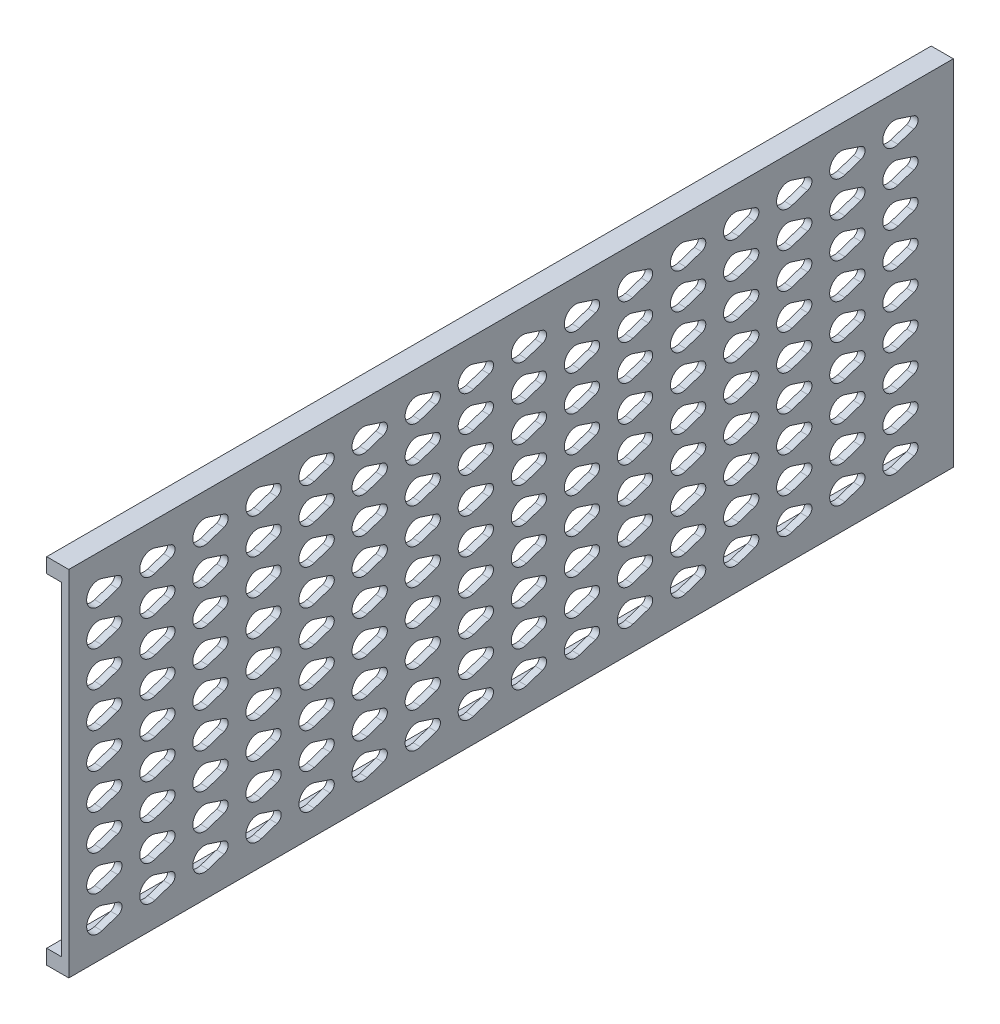
SolidWorks part; units mm, degrees
ref_plane "Front Plane" through (0, 0, 0) normal (1, 0, 0) x (0, 1, 0)
ref_plane "Top Plane" through (0, 0, 0) normal (0, 0, 1) x (0, 1, 0)
ref_plane "Right Plane" through (0, 0, 0) normal (0, 1, 0) x (-1, 0, 0)
sketch "Sketch1" plane through (0, 0, 0) normal (1, 0, 0) x (0, 1, 0)
  line L1 (-76.2, -190.5) -> (76.2, -190.5)
  line L2 (-76.2, -190.5) -> (-76.2, 190.5)
  line L3 (-76.2, 190.5) -> (76.2, 190.5)
  line L4 (76.2, -190.5) -> (76.2, 190.5)
  line L5 (-76.2, -190.5) -> (76.2, 190.5) construction
  line L6 (-76.2, 190.5) -> (76.2, -190.5) construction
  point P0 (0, 0)
  dimension "D1" = 152.4
  dimension "D2" = 381
extrude "Boss-Extrude1" add sketch "Sketch1" along normal blind 3.175
sketch "Sketch2" plane through (0, 0, 0) normal (-1, 0, 0) x (0, -1, 0)
  line L5 (-76.2, 190.5) -> (76.2, 190.5) construction
  line L6 (-76.2, -190.5) -> (-69.85, -190.5)
  line L7 (-76.2, -190.5) -> (-76.2, 190.5)
  line L8 (-76.2, 190.5) -> (-69.85, 190.5)
  line L9 (-69.85, -190.5) -> (-69.85, 190.5)
  line L10 (76.2, -190.5) -> (-76.2, -190.5) construction
  line L11 (76.2, 190.5) -> (69.85, 190.5)
  line L12 (76.2, 190.5) -> (76.2, -190.5)
  line L13 (76.2, -190.5) -> (69.85, -190.5)
  line L14 (69.85, 190.5) -> (69.85, -190.5)
  dimension "D1" = 6.35
  dimension "D2" = 6.35
extrude "Boss-Extrude2" add sketch "Sketch2" along normal blind 6.35
sketch "Sketch3" plane through (3.175, 0, 0) normal (1, 0, 0) x (0, 1, 0)
  line L0 (-65.7055, 176.2252) -> (-63.4277, 169.3611)
  line L1 (-58.4923, 169.3611) -> (-56.2145, 176.2252)
  line L2 (-76.2, 190.5) -> (-76.2, -190.5) construction
  line L3 (76.2, 190.5) -> (-76.2, 190.5) construction
  circle A0 centre (-60.96, 177.8) radius 5
  circle A1 centre (-60.96, 170.18) radius 2.6
  dimension "D1" = 5.2
  dimension "D3" = 10
  dimension "D2" = 7.62
  dimension "D4" = 15.24
  dimension "D5" = 20.32
extrude "Cut-Extrude1" cut sketch "Sketch3" against normal through all both and the other way through all contours A1 L1 A0 L0 | A1 | A0
pattern_linear "LPattern1" count 16 spacing 22.86 along (0, 0, -1) count 9 spacing 15.24 along (0, 1, 0) of "Cut-Extrude1"
